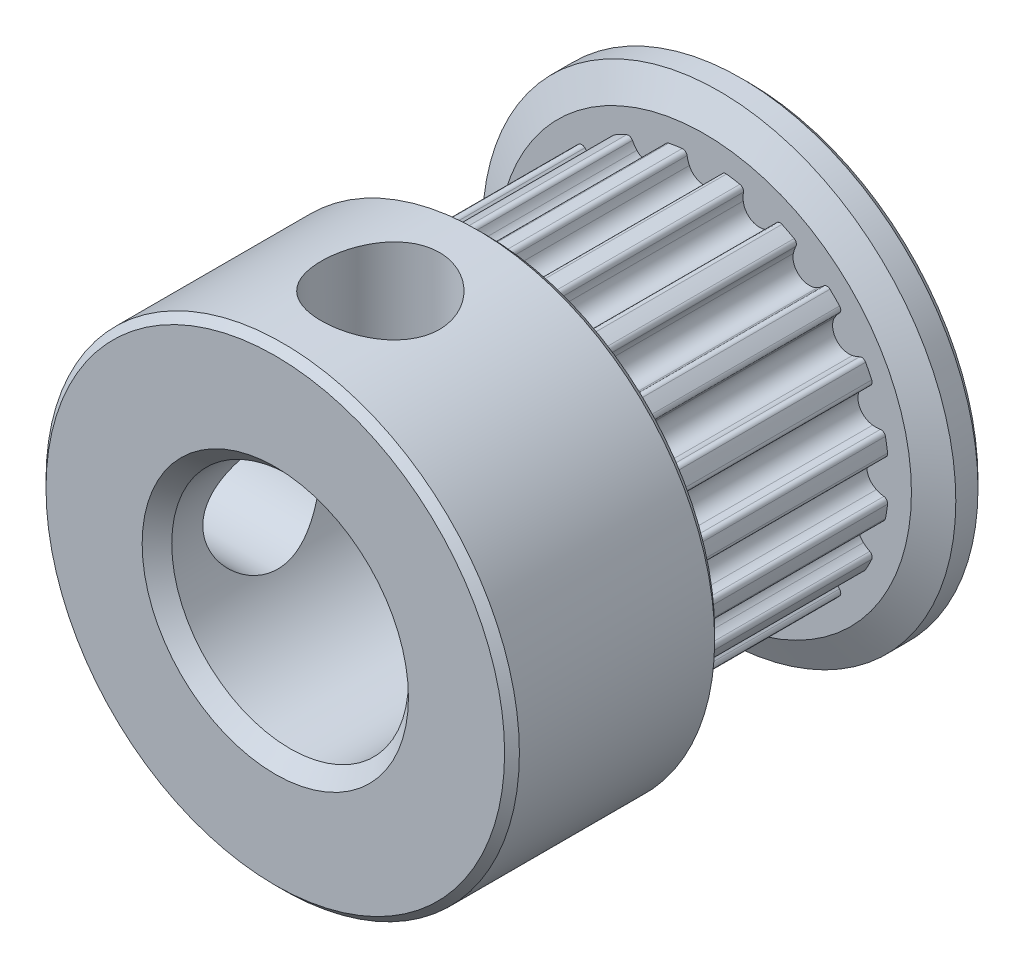
SolidWorks part; units mm, degrees
ref_plane "Front Plane" through (0, 0, 0) normal (0, 0, 1) x (1, 0, 0)
ref_plane "Top Plane" through (0, 0, 0) normal (0, 1, 0) x (1, 0, 0)
ref_plane "Right Plane" through (0, 0, 0) normal (1, 0, 0) x (0, 0, -1)
sketch "Sketch1" plane through (0, 0, 0) normal (0, 0, 1) x (1, 0, 0)
  circle A0 centre (0, 0) radius 6.366
  dimension "D1" = 12.732
extrude "Base" add sketch "Sketch1" along normal blind 7.4
sketch "Sketch2" plane through (0, 0, 7.4) normal (0, 0, 1) x (1, 0, 0)
  line L0 (0, 0) -> (0, 6.239) construction
  line L1 (0, 0) -> (-1.928, 5.9336) construction
  line L2 (-0.976, 6.1622) -> (0, 0) construction
  line L3 (-0.976, 6.1622) -> (-0.9959, 6.2876)
  line L4 (0.976, 6.1622) -> (0.9959, 6.2876)
  arc A1 (-0.5814, 6.0687) -> (-0.5066, 5.8173) centre (0.4062, 6.2258) ccw
  arc A2 (-0.5066, 5.8173) -> (0.5066, 5.8173) centre (0, 6.044) ccw
  arc A3 (-0.5814, 6.0687) -> (-0.7475, 6.1941) centre (-0.7295, 6.0451) ccw
  arc A4 (0.5814, 6.0687) -> (0.5066, 5.8173) centre (-0.4062, 6.2258) cw
  arc A5 (0.5814, 6.0687) -> (0.7475, 6.1941) centre (0.7295, 6.0451) cw
  arc A6 (0.7475, 6.1941) -> (0.976, 6.1622) centre (0, 0) cw
  circle A7 centre (0, 0) radius 6.366 construction
  arc A8 (0.9959, 6.2876) -> (-0.9959, 6.2876) centre (0, 0) ccw
  arc A11 (-0.7475, 6.1941) -> (-0.976, 6.1622) centre (0, 0) ccw
  dimension "D1" = 6.239
  dimension "D3" = 2
  dimension "D4" = 1.11
  dimension "D7" = 0.3
  dimension "D2" = 18
  dimension "D5" = 0.195
  dimension "D6" = 9
  dimension "D8" = 0.4062
extrude "ToothCut" cut sketch "Sketch2" against normal through all
pattern_circular "TeethCuts" count 20 over 360 about axis through (0, 0, 0) along (0, 0, 1) of "ToothCut"
sketch "Sketch3" plane through (0, 0, 0) normal (0, 1, 0) x (1, 0, 0)
  line L0 (0, 0) -> (0, 1.5)
  line L1 (0, 1.5) -> (-8, 1.5)
  line L2 (-8, 1.5) -> (-8, 0.5)
  line L3 (-7, 0) -> (0, 0)
  line L4 (0, -7.4) -> (-8, -7.4)
  line L5 (-0.5066, -7.4) -> (0.5066, -7.4) construction
  line L6 (-8, -7.4) -> (-8, -14.5)
  line L7 (-8, -14.5) -> (0, -14.5)
  line L8 (0, -14.5) -> (0, -7.4)
  line L9 (-8, 0.5) -> (-7, 0)
  point P5 (-8, 0)
  dimension "D1" = 16
  dimension "D2" = 1.5
  dimension "D3" = 0.5
  dimension "D4" = 1
  dimension "D5" = 8
revolve "Body" add sketch "Sketch3" angle 360 about L8
sketch "Sketch4" plane through (0, 0, 0) normal (0, 0, 1) x (1, 0, 0)
  circle A0 centre (0, 0) radius 4
  dimension "D1" = 8
extrude "ShaftHole" cut sketch "Sketch4" along normal through all both and the other way through all
sketch "Sketch5" plane through (0, 0, 0) normal (0, 1, 0) x (1, 0, 0)
  line L0 (-8, -7.4) -> (-8, -14.5) construction
  line L3 (-8, -14.5) -> (8, -14.5) construction
  circle A0 centre (0, -10.95) radius 2
  dimension "D1" = 4
  dimension "D2" = 8
  dimension "D3" = 3.55
extrude "FixingHole" cut sketch "Sketch5" along normal through all
pattern_circular "CirPattern1" count 2 over 90 about axis through (0, 0, 14.5) along (0, 0, -1) of "FixingHole"
chamfer "Chamfer1" distance 0.5 angle 45 2 edges at (4, 0, -1.5) (4, 0, 14.5)
chamfer "Chamfer2" distance 0.25 angle 45 3 edges at (8, 0, -1.5) (8, 0, 7.4) (8, 0, 14.5)
